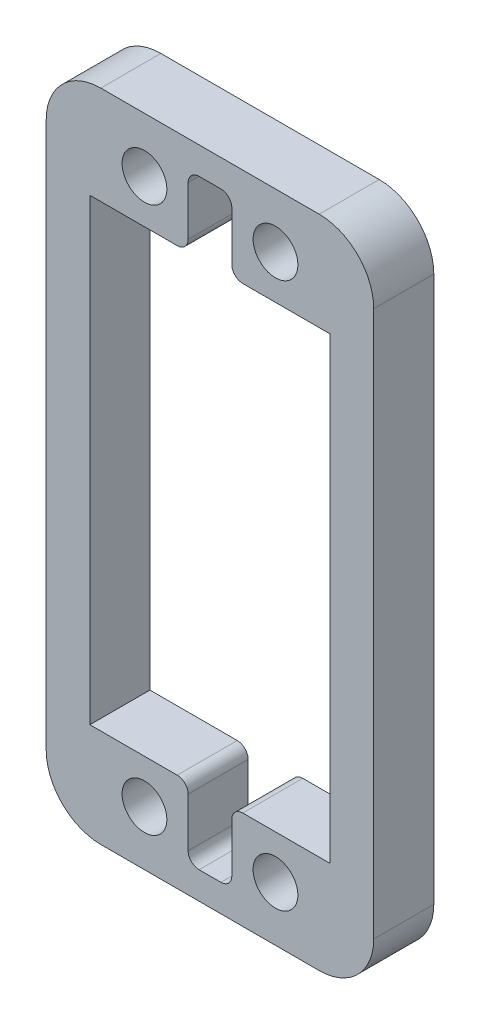
SolidWorks part; units mm, degrees
ref_plane "Alzado" through (0, 0, 0) normal (0, 0, 1) x (1, 0, 0)
ref_plane "Planta" through (0, 0, 0) normal (0, 1, 0) x (1, 0, 0)
ref_plane "Vista lateral" through (0, 0, 0) normal (1, 0, 0) x (0, 0, -1)
sketch "Croquis1" plane through (0, 0, 0) normal (0, 0, 1) x (1, 0, 0)
  line L0 (-15, 30) -> (15, 30)
  line L1 (15, 30) -> (15, -30)
  line L2 (15, -30) -> (-15, -30)
  line L3 (-15, -30) -> (-15, 30)
  line L4 (0, 0) -> (3.1755, 0) construction
  line L5 (0, 0) -> (0, 1.2752) construction
  dimension "D1" = 60
  dimension "D2" = 30
extrude "Saliente-Extruir1" add sketch "Croquis1" along normal blind 5.5
sketch "Croquis2" plane through (0, 0, 0) normal (0, 0, -1) x (-1, 0, 0)
  line L0 (-11, 21) -> (11, 21)
  line L1 (11, 21) -> (11, -21)
  line L2 (11, -21) -> (-11, -21)
  line L3 (-11, -21) -> (-11, 21)
  line L4 (0, 0) -> (17.9824, 0) construction
  line L5 (0, 0) -> (0, 11.2002) construction
  dimension "D1" = 22
  dimension "D2" = 42
extrude "Cortar-Extruir1" cut sketch "Croquis2" against normal through all
sketch "Croquis3" plane through (0, 0, 0) normal (0, 0, -1) x (-1, 0, 0)
  line L0 (0, 0) -> (-26.2125, 0) construction
  line L1 (0, 0) -> (0, 9.0898) construction
  line L2 (-2, 21) -> (-2, 27.5)
  line L3 (11, 21) -> (-11, 21) construction
  line L4 (-2, 27.5) -> (2, 27.5)
  line L5 (2, 27.5) -> (2, -27.5)
  line L6 (2, -27.5) -> (-2, -27.5)
  line L7 (-2, -27.5) -> (-2, 21)
  circle A0 centre (-6, 25) radius 2.05
  circle A1 centre (6, 25) radius 2.05
  circle A2 centre (-6, -25) radius 2.05
  circle A3 centre (6, -25) radius 2.05
  dimension "D1" = 4.1
  dimension "D2" = 4.1
  dimension "D3" = 4.1
  dimension "D4" = 4.1
  dimension "D5" = 12
  dimension "D6" = 12
  dimension "D7" = 50
  dimension "D8" = 25
  dimension "D9" = 4
  dimension "D10" = 55
extrude "Cortar-Extruir2" cut sketch "Croquis3" against normal through all
fillet "Redondeo1" radius 5 4 edges at (-15, -30, 2.75) (15, -30, 2.75) (15, 30, 2.75) (-15, 30, 2.75)
fillet "Redondeo3" radius 1 8 edges at (-2, -27.5, 2.75) (-2, -21, 2.75) (2, -21, 2.75) (2, -27.5, 2.75) (2, 27.5, 2.75) (-2, 27.5, 2.75) (2, 21, 2.75) (-2, 21, 2.75)
ref_plane "Plano1" through (0, 0, 5.5) normal (0, 0, 1) x (1, 0, 0)
